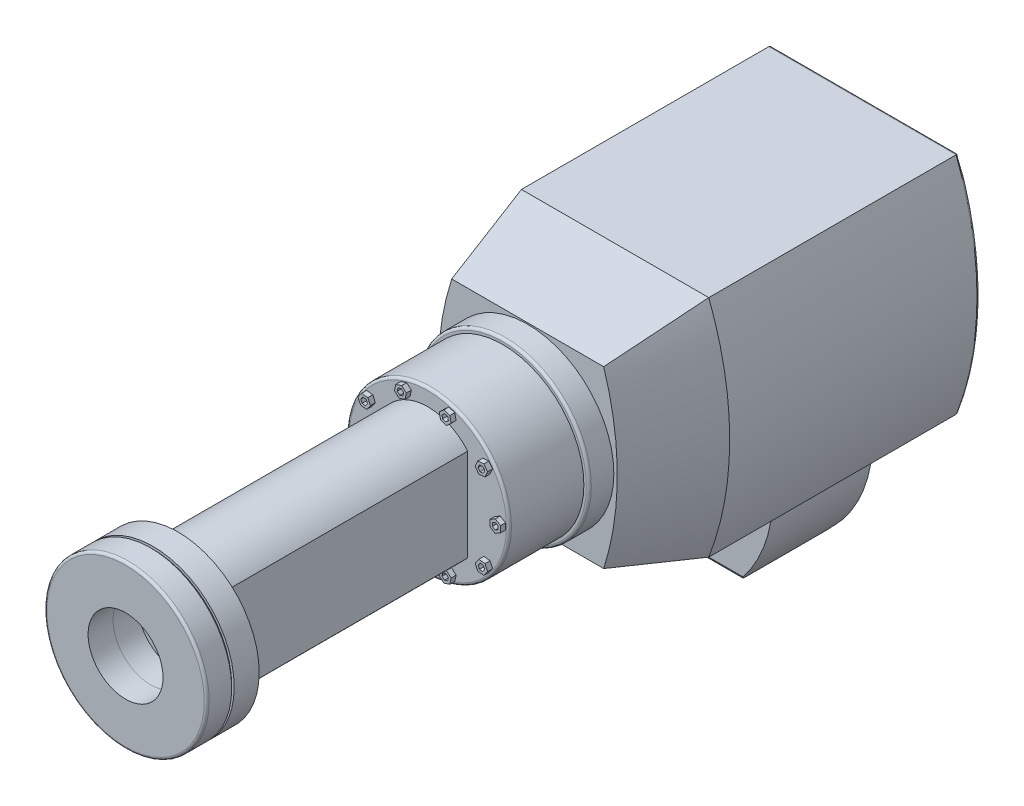
SolidWorks part; units mm, degrees
ref_plane "Front Plane" through (0, 0, 0) normal (0, 0, 1) x (1, 0, 0)
ref_plane "Top Plane" through (0, 0, 0) normal (0, 1, 0) x (1, 0, 0)
ref_plane "Right Plane" through (0, 0, 0) normal (1, 0, 0) x (0, 0, -1)
sketch "Sketch1" plane through (0, 0, 0) normal (0, 0, 1) x (1, 0, 0)
  line L0 (0, -45) -> (0, 45) construction
  line L1 (-37.5, 45) -> (37.5, 45)
  line L2 (-37.5, -45) -> (37.5, -45)
  arc A0 (-37.5, 45) -> (-37.5, -45) centre (79.119, 0) ccw
  arc A1 (37.5, 45) -> (37.5, -45) centre (-79.119, 0) cw
  point P4 (0, 0)
  point P7 (0, 45)
  point P10 (0, -45)
  dimension "D4" = 125
  dimension "D1" = 90
  dimension "D2" = 75
  dimension "D3" = 75
extrude "Boss-Extrude1" add sketch "Sketch1" along normal blind 100
sketch "Sketch2" plane through (0, 0, 100) normal (0, 0, 1) x (1, 0, 0)
  line L2 (37.5, 45) -> (-37.5, 45)
  line L3 (-37.5, -45) -> (37.5, -45)
  line L4 (37.5, 45) -> (-37.5, 45)
  line L5 (-37.5, -45) -> (37.5, -45)
  arc A2 (37.5, -45) -> (37.5, 45) centre (-79.119, 0) ccw
  arc A3 (-37.5, 45) -> (-37.5, -45) centre (79.119, 0) ccw
  arc A4 (37.5, -45) -> (37.5, 45) centre (-79.119, 0) ccw
  arc A5 (-37.5, 45) -> (-37.5, -45) centre (79.119, 0) ccw
  dimension "D1" = 0
ref_plane "Plane1" through (0, 0, 135) normal (0, 0, 1) x (1, 0, 0)
sketch "Sketch3" plane through (0, 0, 135) normal (0, 0, 1) x (1, 0, 0)
  line L4 (30.4255, 35) -> (-30.4255, 35)
  line L5 (-30.4255, -35) -> (30.4255, -35)
  line L6 (30.4255, 35) -> (-30.4255, 35)
  line L7 (-30.4255, -35) -> (30.4255, -35)
  arc A4 (-30.4255, 35) -> (-30.4255, -35) centre (79.119, 0) ccw
  arc A5 (30.4255, -35) -> (30.4255, 35) centre (-79.119, 0) ccw
  arc A6 (-30.4255, 35) -> (-30.4255, -35) centre (79.119, 0) ccw
  arc A7 (30.4255, -35) -> (30.4255, 35) centre (-79.119, 0) ccw
  dimension "D1" = 10
loft "Loft1" add profiles "Sketch3", "Sketch2"
sketch "Sketch4" plane through (0, 0, 135) normal (0, 0, 1) x (1, 0, 0)
  circle A0 centre (0, 0) radius 34.5
  dimension "D1" = 69
extrude "Boss-Extrude2" add sketch "Sketch4" along normal blind 10
sketch "Sketch5" plane through (0, 0, 145) normal (0, 0, 1) x (1, 0, 0)
  circle A2 centre (0, 0) radius 32.5
  circle A3 centre (0, 0) radius 32.5
  dimension "D1" = 2
extrude "Boss-Extrude3" add sketch "Sketch5" along normal blind 30
sketch "Sketch6" plane through (0, 0, 175) normal (0, 0, 1) x (1, 0, 0)
  line L0 (0, 0) -> (29, 0) construction
  line L1 (29, 1.3453) -> (27.8349, 0.6726)
  line L2 (29, 2.5) -> (26.8349, 1.25)
  line L3 (26.8349, 1.25) -> (26.8349, -1.25)
  line L4 (26.8349, -1.25) -> (29, -2.5)
  line L5 (29, -2.5) -> (31.1651, -1.25)
  line L6 (31.1651, -1.25) -> (31.1651, 1.25)
  line L7 (31.1651, 1.25) -> (29, 2.5)
  line L8 (27.8349, 0.6726) -> (27.8349, -0.6726)
  line L9 (27.8349, -0.6726) -> (29, -1.3453)
  line L10 (29, -1.3453) -> (30.1651, -0.6726)
  line L11 (30.1651, -0.6726) -> (30.1651, 0.6726)
  line L12 (30.1651, 0.6726) -> (29, 1.3453)
  circle A0 centre (29, 0) radius 2.1651 construction
  dimension "D1" = 29
  dimension "D2" = 5
  dimension "D3" = 1
extrude "Boss-Extrude4" add sketch "Sketch6" along normal blind 2
pattern_circular "CirPattern1" count 10 over 360 about axis through (0, 0, 0) along (0, 0, 1) of "Boss-Extrude4"
sketch "Sketch7" plane through (0, 0, 175) normal (0, 0, 1) x (1, 0, 0)
  line L0 (0, 0) -> (16, 0) construction
  line L1 (0, 0) -> (0, 21.2483) construction
  line L2 (0, 0) -> (0, -18.7463) construction
  line L3 (16, -18.5) -> (16, 18.5)
  line L4 (-16, -18.5) -> (-16, 18.5)
  arc A0 (-16, 18.5) -> (16, 18.5) centre (0, 4.8985) cw
  arc A1 (-16, -18.5) -> (16, -18.5) centre (0, -4.8985) ccw
  point P8 (16, 0)
  dimension "D3" = 21
  dimension "D1" = 37
  dimension "D2" = 32
extrude "Boss-Extrude5" add sketch "Sketch7" along normal blind 100
sketch "Sketch8" plane through (0, 0, 275) normal (0, 0, 1) x (1, 0, 0)
  circle A0 centre (0, 0) radius 32.5 construction
  circle A1 centre (0, 0) radius 32.5
extrude "Boss-Extrude6" add sketch "Sketch8" along normal blind 10
sketch "Sketch9" plane through (0, 0, 285) normal (0, 0, 1) x (1, 0, 0)
  circle A2 centre (0, 0) radius 31.5
  circle A3 centre (0, 0) radius 31.5
  dimension "D1" = 1
extrude "Boss-Extrude7" add sketch "Sketch9" along normal blind 1
sketch "Sketch10" plane through (0, 0, 286) normal (0, 0, 1) x (1, 0, 0)
  circle A1 centre (0, 0) radius 32.5 construction
  circle A4 centre (0, 0) radius 32.5
extrude "Boss-Extrude8" add sketch "Sketch10" along normal blind 10 separate body
ref_plane "Plane2" through (-37.5, 0, 0) normal (1, 0, 0) x (0, 0, -1)
sketch "Sketch11" plane through (-37.5, 0, 0) normal (1, 0, 0) x (0, 0, -1)
  line L0 (-100, -45) -> (0, -45) construction
  circle A0 centre (-50, -45) radius 42.5
  dimension "D1" = 85
extrude "Boss-Extrude9" add sketch "Sketch11" along normal mid plane 21
sketch "Sketch12" plane through (-27, 0, 0) normal (1, 0, 0) x (0, 0, -1)
  line L0 (-50, -45) -> (-50, -75) construction
  line L1 (-100, -45) -> (0, -45) construction
  line L2 (-70, -45) -> (-70, -75)
  line L3 (-30, -45) -> (-30, -75)
  line L4 (-70, -45) -> (-30, -45)
  arc A0 (-70, -75) -> (-30, -75) centre (-50, -60.3189) ccw
  dimension "D4" = 24.81
  dimension "D1" = 30
  dimension "D2" = 20
  dimension "D3" = 20
extrude "Boss-Extrude10" add sketch "Sketch12" along normal blind 35
ref_plane "Plane3" through (0, 0, 50) normal (0, 0, 1) x (1, 0, 0)
sketch "Sketch13" plane through (0, 0, 50) normal (0, 0, 1) x (1, 0, 0)
  line L0 (8, -45) -> (8, -87)
  line L1 (8, -45) -> (33, -45)
  line L2 (-37.5, -45) -> (37.5, -45) construction
  arc A0 (8, -87) -> (33, -45) centre (-21.8393, -40.7981) ccw
  dimension "D3" = 55
  dimension "D1" = 25
  dimension "D2" = 42
extrude "Boss-Extrude11" add sketch "Sketch13" along normal mid plane 40
sketch "Sketch14" plane through (8, 0, 0) normal (-1, 0, 0) x (0, 0, 1)
  line L3 (70, -87) -> (70, -75)
  line L4 (30, -75) -> (30, -87)
  line L5 (30, -87) -> (70, -87)
  line L6 (70, -87) -> (70, -75)
  line L7 (30, -75) -> (30, -87)
  line L8 (30, -87) -> (70, -87)
  arc A1 (30, -75) -> (70, -75) centre (50, -60.3189) ccw
  arc A2 (30, -75) -> (70, -75) centre (50, -60.3189) ccw
  dimension "D1" = 0
extrude "Cut-Extrude1" cut sketch "Sketch14" against normal through all
fillet "Fillet1" radius 1 8 edges at (0, 45, 0) (-45.881, 0, 0) (0, -45, 0) (45.881, 0, 0) (32.5, 0, 175) (34.5, 0, 145) (-48, -45, 7.5) (-27, -87.5, 50)
fillet "Fillet2" radius 1 1 edges at (32.5, 0, 296)
sketch "Sketch15" plane through (0, 0, 296) normal (0, 0, 1) x (1, 0, 0)
  circle A0 centre (0, 0) radius 15
  dimension "D1" = 30
extrude "Cut-Extrude2" cut sketch "Sketch15" against normal blind 20
sketch "Sketch16" plane through (-48, 0, 0) normal (-1, 0, 0) x (0, 0, 1)
  circle A0 centre (50, -45) radius 15
  dimension "D1" = 30
extrude "Cut-Extrude3" cut sketch "Sketch16" against normal blind 20
